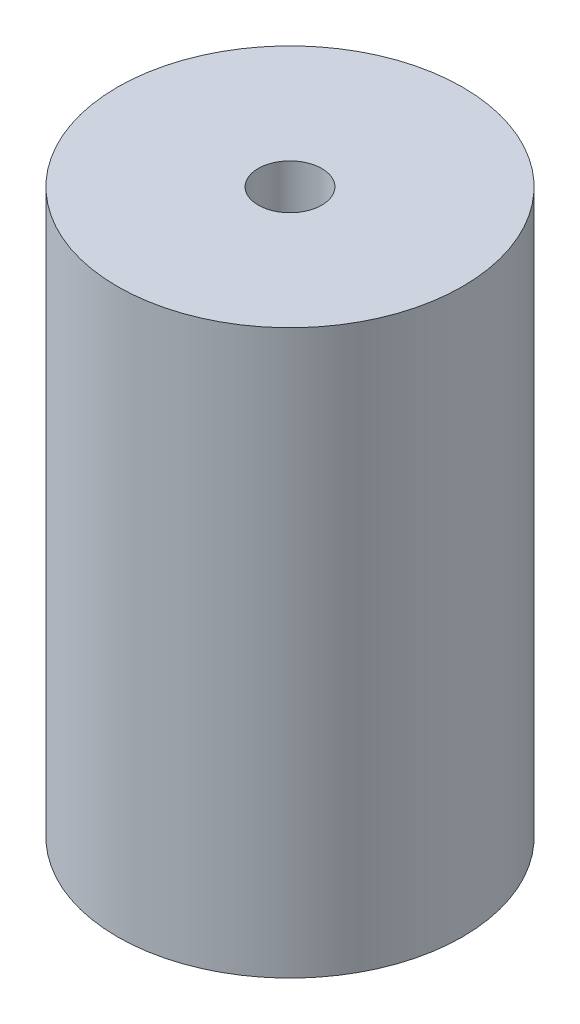
SolidWorks part; units mm, degrees
material "Epoxy, Unfilled"
ref_plane "Front Plane" through (0, 0, 0) normal (0, 0, 1) x (1, 0, 0)
ref_plane "Top Plane" through (0, 0, 0) normal (0, 1, 0) x (1, 0, 0)
ref_plane "Right Plane" through (0, 0, 0) normal (1, 0, 0) x (0, 0, -1)
sketch "Sketch1" plane through (0, 0, 0) normal (0, 1, 0) x (1, 0, 0)
  circle A0 centre (0, 0) radius 19
  circle A1 centre (0, 0) radius 3.5
extrude "Boss-Extrude1" add sketch "Sketch1" along normal blind 62
